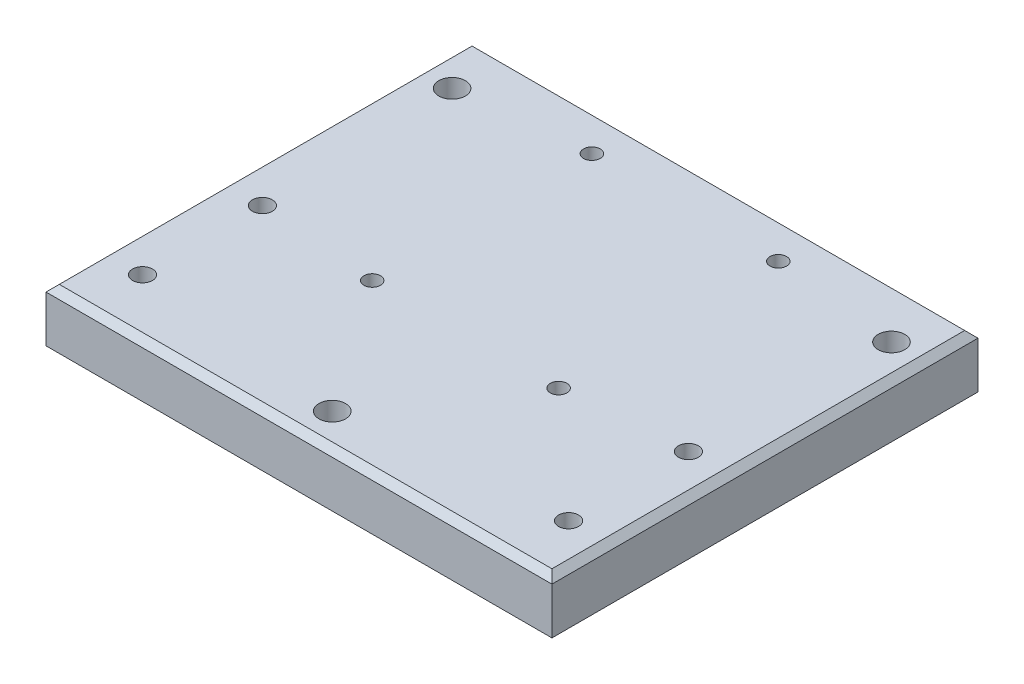
SolidWorks part; units mm, degrees
material "Cast Carbon Steel"
ref_plane "Front Plane" through (0, 0, 0) normal (0, 0, 1) x (1, 0, 0)
ref_plane "Top Plane" through (0, 0, 0) normal (0, 1, 0) x (1, 0, 0)
ref_plane "Right Plane" through (0, 0, 0) normal (1, 0, 0) x (0, 0, -1)
sketch "Sketch1" plane through (0, 0, 0) normal (0, 1, 0) x (1, 0, 0)
  line L1 (-38, 32) -> (38, 32)
  line L2 (-38, 32) -> (-38, -32)
  line L3 (-38, -32) -> (38, -32)
  line L4 (38, 32) -> (38, -32)
  line L5 (-38, 32) -> (38, -32) construction
  line L6 (-38, -32) -> (38, 32) construction
  point P0 (0, 0)
  dimension "D1" = 64
  dimension "D2" = 76
extrude "Boss-Extrude1" add sketch "Sketch1" along normal blind 8
hole_wizard "M3 Tapped Hole1" positions "Sketch2" profile "Sketch3" tap size "M3" standard "ISO" end condition through all
sketch "Sketch2" plane through (0, 8, 0) normal (0, 1, 0) x (1, 0, 0)
  line L0 (-38, -32) -> (38, -32) construction
  line L2 (0, 0) -> (0, 33.9196) construction
  point P0 (-14, 26)
  dimension "D1" = 58
  dimension "D2" = 14
sketch "Sketch3" plane through (-14, 8, -26) normal (1, 0, 0) x (0, 0, 1)
  line L0 (0, 0) -> (0, 8)
  line L1 (0, 8) -> (1.25, 8)
  line L2 (1.25, 8) -> (1.25, 0)
  line L5 (1.25, 0) -> (0, 0)
  line L11 (0, -6.35) -> (0, 107.95) construction
  dimension "Thru Tap Drill Dia." = 2.5
  dimension "Thru Tap Drill Depth" = 8
cosmetic thread "Hole Thread1" parameters "D2"=3
pattern_linear "LPattern2" count 2 spacing 28 along (1, 0, 0) count 2 spacing 33 along (0, 0, 1) of "M3 Tapped Hole1"
sketch "Sketch5" plane through (0, 8, 0) normal (0, 1, 0) x (1, 0, 0)
  line L0 (0, 25.4508) -> (0, -27.6562) construction
  line L1 (-38, -32) -> (38, -32) construction
  line L2 (38, 32) -> (-38, 32) construction
  circle A0 centre (-33, 24) radius 2
  circle A1 centre (33, 24) radius 2
  circle A2 centre (0, -27) radius 2
  dimension "D1" = 4
  dimension "D2" = 33
  dimension "D4" = 5
  dimension "D6" = 8
  dimension "D3" = 33
  dimension "D5" = 8
extrude "Cut-Extrude1" cut sketch "Sketch5" against normal through all
chamfer "Chamfer1" distance 1 angle 45 4 edges at (38, 8, 0) (0, 8, 32) (-38, 8, 0) (0, 8, -32)
sketch "Sketch6" plane through (0, 8, 0) normal (0, 1, 0) x (1, 0, 0)
  line L0 (38, -32) -> (-38, -32) construction
  circle A0 centre (32, -5.5) radius 1.5
  circle A1 centre (32, -23.5) radius 1.5
  circle A2 centre (-32, -23.5) radius 1.5
  circle A3 centre (-32, -5.5) radius 1.5
  dimension "D1" = 3
  dimension "D3" = 32
  dimension "D2" = 64
  dimension "D4" = 18
  dimension "D5" = 8.5
extrude "Cut-Extrude2" cut sketch "Sketch6" against normal blind 10
cosmetic thread "Cosmetic Thread1" parameters "D2"=9
cosmetic thread "Cosmetic Thread2" parameters "D2"=9
cosmetic thread "Cosmetic Thread3" parameters "D2"=9
cosmetic thread "Cosmetic Thread4" parameters "D2"=9
